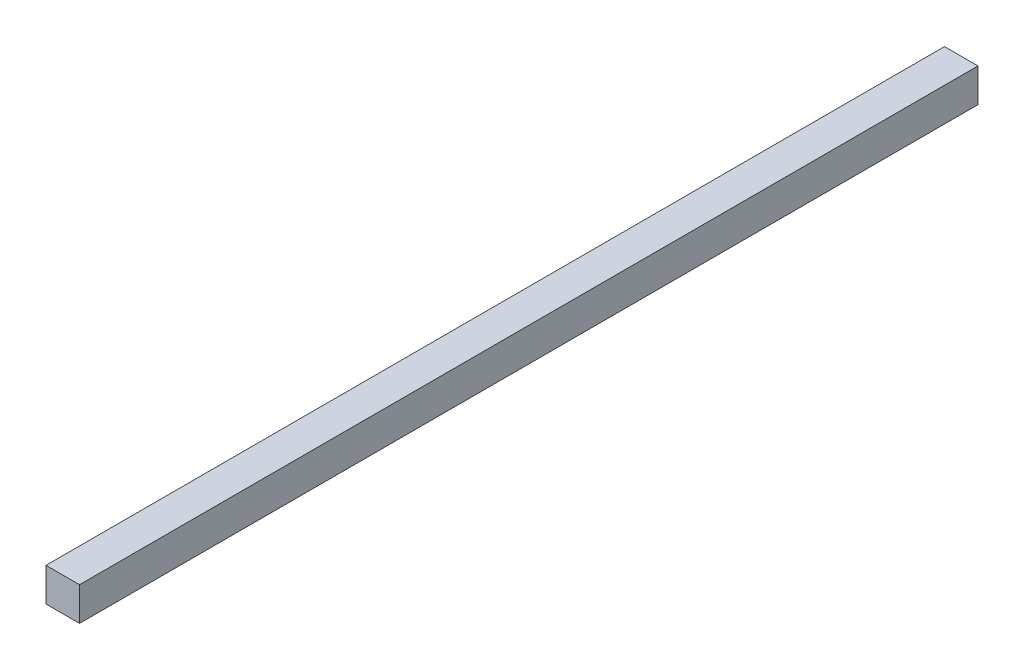
SolidWorks part; units mm, degrees
ref_plane "Front Plane" through (0, 0, 0) normal (0, 0, 1) x (1, 0, 0)
ref_plane "Top Plane" through (0, 0, 0) normal (0, 1, 0) x (1, 0, 0)
ref_plane "Right Plane" through (0, 0, 0) normal (1, 0, 0) x (0, 0, -1)
sketch "Sketch2" plane through (0, 0, 0) normal (1, 0, 0) x (0, 0, -1)
  line L0 (0, 0) -> (37.8511, 0)
  line L1 (37.8511, 0) -> (37.8511, 1.4122)
  line L2 (37.8511, 1.4122) -> (0, 1.4122)
  line L3 (0, 1.4122) -> (0, 0)
extrude "Boss-Extrude1" add sketch "Sketch2" along normal blind 1.4122
